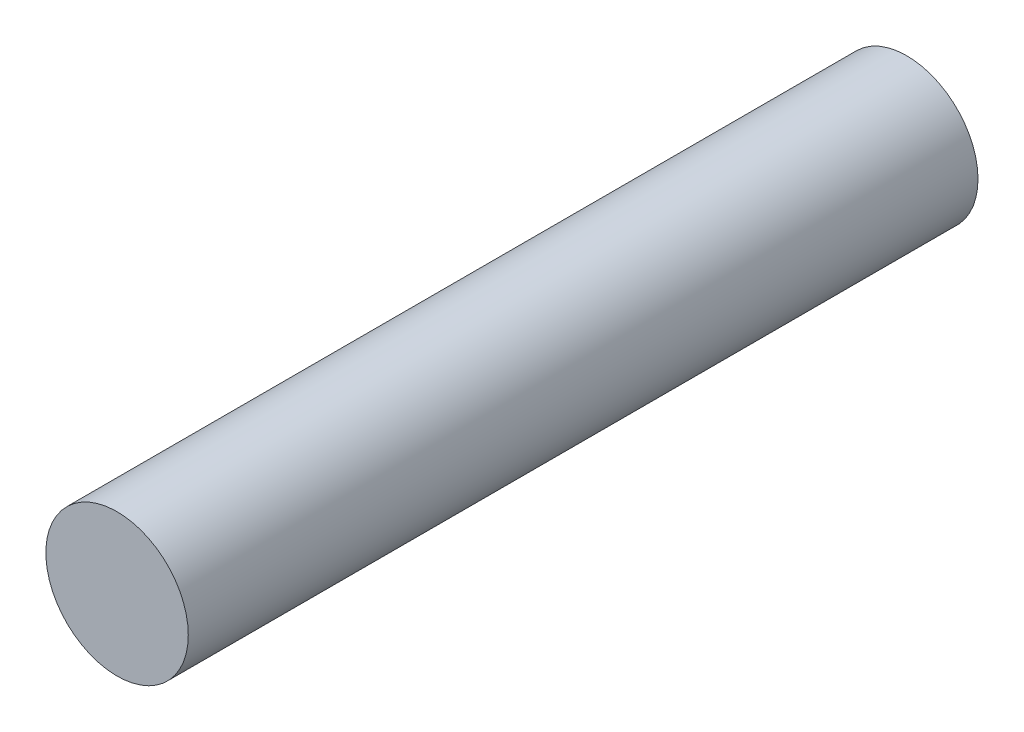
SolidWorks part; units mm, degrees
ref_plane "Front Plane" through (0, 0, 0) normal (0, 0, 1) x (1, 0, 0)
ref_plane "Top Plane" through (0, 0, 0) normal (0, 1, 0) x (1, 0, 0)
ref_plane "Right Plane" through (0, 0, 0) normal (1, 0, 0) x (0, 0, -1)
sketch "Sketch1" plane through (0, 0, 0) normal (0, 0, 1) x (1, 0, 0)
  circle A0 centre (0, 0) radius 2.7051
  dimension "D1" = 5.4102
extrude "Boss-Extrude1" add sketch "Sketch1" along normal blind 30
